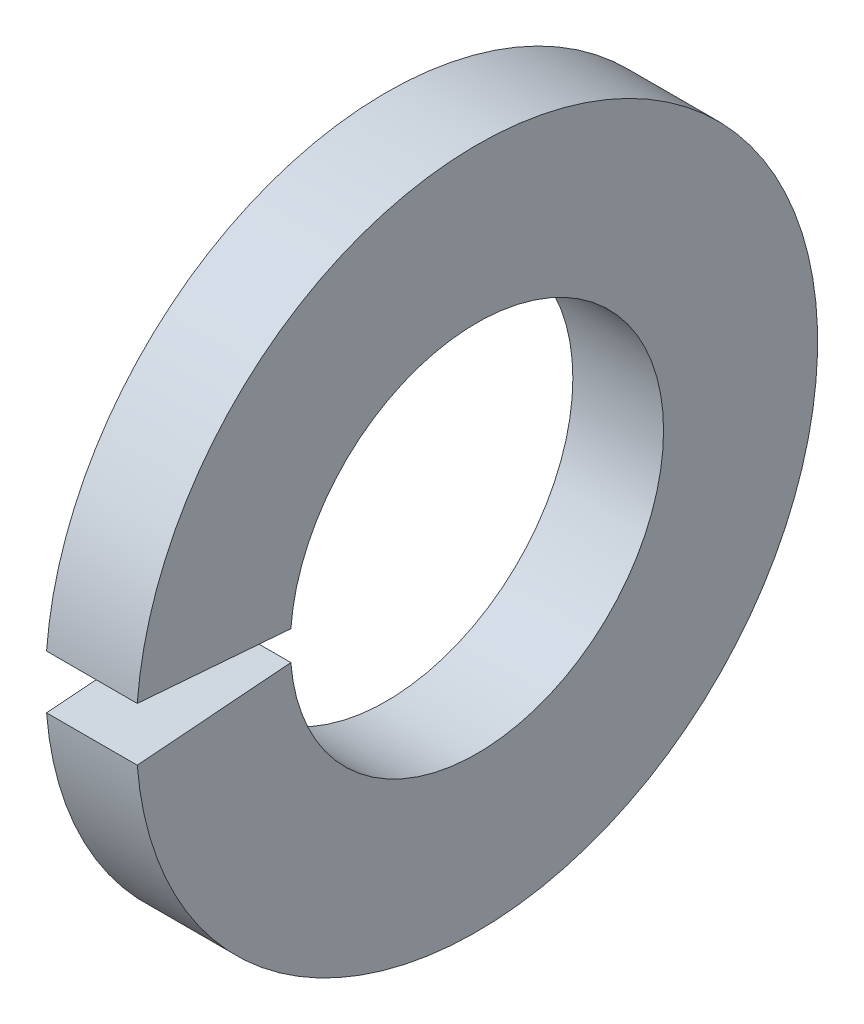
SolidWorks part; units mm, degrees
material "Chrome Stainless Steel"
ref_plane "Front Plane" through (0, 0, 0) normal (0, 0, 1) x (1, 0, 0)
ref_plane "Top Plane" through (0, 0, 0) normal (0, 1, 0) x (1, 0, 0)
ref_plane "Right Plane" through (0, 0, 0) normal (1, 0, 0) x (0, 0, -1)
ref_plane "Plane1" through (0, 0, 0) normal (0, 0.9969, 0.0785) x (-1, 0, 0)
sketch "Sketch1" plane through (0, 0, 0) normal (0, 0.9969, 0.0785) x (-1, 0, 0)
  line L0 (1.9812, 7.4422) -> (0, 7.4422)
  line L1 (0, 7.4422) -> (0, 4.0767)
  line L2 (0, 4.0767) -> (1.9812, 4.0767)
  line L3 (1.9812, 4.0767) -> (1.9812, 7.4422)
  line L4 (0, 0) -> (1.9812, 0) construction
revolve "Revolve1" add sketch "Sketch1" angle 351 about L4
